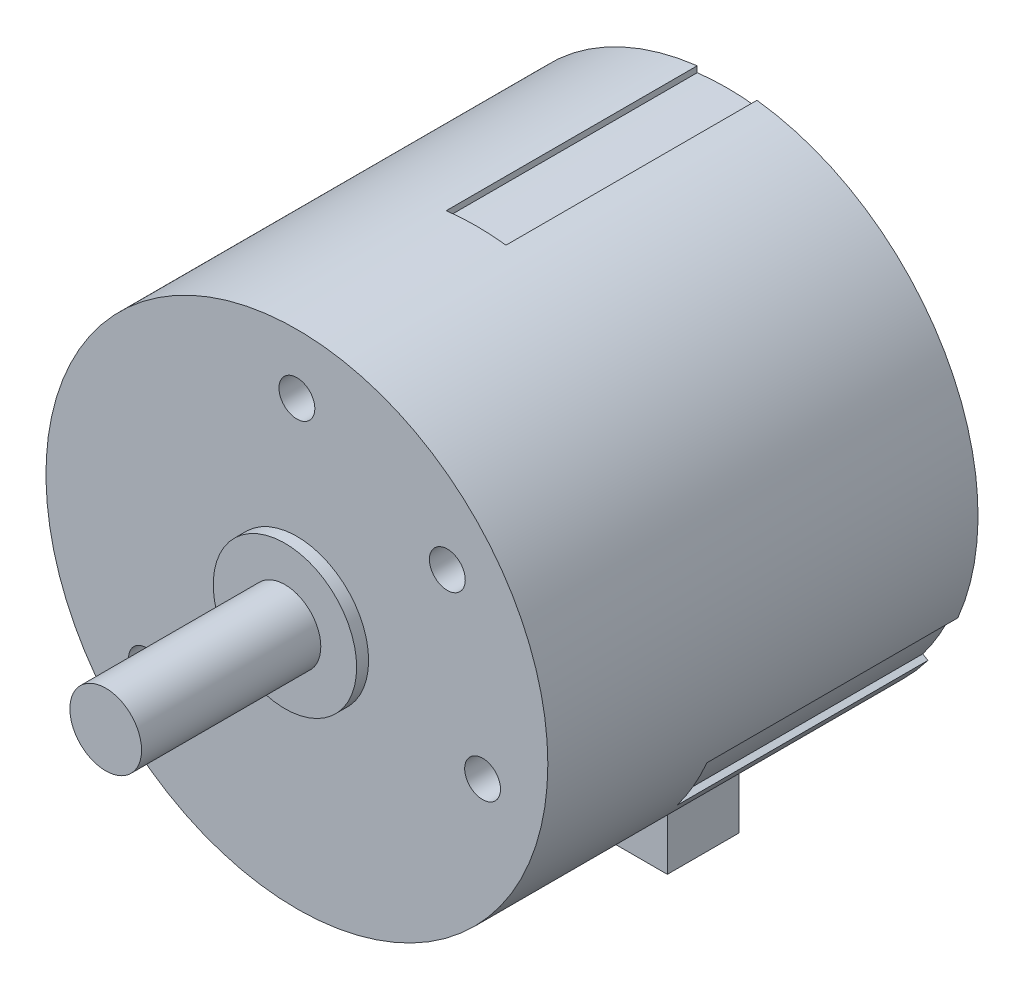
SolidWorks part; units mm, degrees
ref_plane "前视基准面" through (0, 0, 0) normal (0, 0, 1) x (1, 0, 0)
ref_plane "上视基准面" through (0, 0, 0) normal (0, 1, 0) x (1, 0, 0)
ref_plane "右视基准面" through (0, 0, 0) normal (1, 0, 0) x (0, 0, -1)
other "Configuration Table"
sketch "草图1" plane through (0, 0, 0) normal (0, 0, 1) x (1, 0, 0)
  circle A0 centre (0, 0) radius 21
extrude "凸台-拉伸1" add sketch "草图1" along normal blind 15
sketch "草图2" plane through (0, 0, 0) normal (0, 0, -1) x (-1, 0, 0)
  line L0 (2.5, 20.8507) -> (2.5, 20.347)
  line L1 (0, 8.25) -> (0, -8.25) construction
  line L2 (-2.5, 20.8507) -> (-2.5, 20.347)
  line L3 (19.3072, -8.2603) -> (18.871, -8.0084)
  line L4 (16.8072, -12.5904) -> (16.371, -12.3386)
  line L5 (-16.8072, -12.5904) -> (-16.371, -12.3386)
  line L6 (-19.3072, -8.2603) -> (-18.871, -8.0084)
  line L7 (15, -13.9732) -> (15, -14.6969)
  line L8 (-15, -13.9732) -> (-15, -14.6969)
  arc A0 (-2.5, 20.8507) -> (-19.3072, -8.2603) centre (0, 0) ccw
  circle A1 centre (0, 0) radius 21 construction
  arc A2 (-18.871, -8.0084) -> (-16.371, -12.3386) centre (0, 0) ccw
  arc A3 (19.3072, -8.2603) -> (2.5, 20.8507) centre (0, 0) ccw
  arc A4 (-16.8072, -12.5904) -> (-15, -14.6969) centre (0, 0) ccw
  arc A5 (15, -14.6969) -> (16.8072, -12.5904) centre (0, 0) ccw
  arc A6 (-15, -13.9732) -> (15, -13.9732) centre (0, 0) ccw
  arc A7 (16.371, -12.3386) -> (18.871, -8.0084) centre (0, 0) ccw
  arc A8 (2.5, 20.347) -> (-2.5, 20.347) centre (0, 0) ccw
  point P22 (0, 0)
  dimension "D1" = 5
  dimension "D2" = 3
  dimension "D3" = 30
extrude "凸台-拉伸2" add sketch "草图2" along normal blind 6
sketch "草图4" plane through (0, 0, -6) normal (0, 0, -1) x (-1, 0, 0)
  line L0 (10, -17.8955) -> (10, -24)
  line L1 (0, 11.55) -> (0, -11.55) construction
  line L2 (-10, -17.8955) -> (-10, -24)
  line L3 (-10, -24) -> (10, -24)
  line L8 (2.5, 20.8507) -> (2.5, 20.347)
  line L9 (-2.5, 20.347) -> (-2.5, 20.8507)
  line L10 (-19.3072, -8.2603) -> (-18.871, -8.0084)
  line L11 (-16.371, -12.3386) -> (-16.8072, -12.5904)
  line L12 (-15, -14.6969) -> (-15, -13.9732)
  line L13 (15, -13.9732) -> (15, -14.6969)
  line L14 (16.8072, -12.5904) -> (16.371, -12.3386)
  line L15 (18.871, -8.0084) -> (19.3072, -8.2603)
  line L16 (2.5, 20.8507) -> (2.5, 20.347)
  line L17 (-2.5, 20.347) -> (-2.5, 20.8507)
  line L18 (-19.3072, -8.2603) -> (-18.871, -8.0084)
  line L19 (-16.371, -12.3386) -> (-16.8072, -12.5904)
  line L20 (-15, -14.6969) -> (-15, -13.9732)
  line L21 (15, -13.9732) -> (15, -14.6969)
  line L22 (16.8072, -12.5904) -> (16.371, -12.3386)
  line L23 (18.871, -8.0084) -> (19.3072, -8.2603)
  arc A0 (10, -17.8955) -> (15, -13.9732) centre (0, 0) ccw
  arc A8 (19.3072, -8.2603) -> (2.5, 20.8507) centre (0, 0) ccw
  arc A9 (2.5, 20.347) -> (-2.5, 20.347) centre (0, 0) ccw
  arc A10 (-2.5, 20.8507) -> (-19.3072, -8.2603) centre (0, 0) ccw
  arc A11 (-18.871, -8.0084) -> (-16.371, -12.3386) centre (0, 0) ccw
  arc A12 (-16.8072, -12.5904) -> (-15, -14.6969) centre (0, 0) ccw
  arc A13 (-15, -13.9732) -> (15, -13.9732) centre (0, 0) ccw
  arc A14 (15, -14.6969) -> (16.8072, -12.5904) centre (0, 0) ccw
  arc A15 (16.371, -12.3386) -> (18.871, -8.0084) centre (0, 0) ccw
  arc A16 (19.3072, -8.2603) -> (2.5, 20.8507) centre (0, 0) ccw
  arc A17 (2.5, 20.347) -> (-2.5, 20.347) centre (0, 0) ccw
  arc A18 (-2.5, 20.8507) -> (-19.3072, -8.2603) centre (0, 0) ccw
  arc A19 (-18.871, -8.0084) -> (-16.371, -12.3386) centre (0, 0) ccw
  arc A20 (-16.8072, -12.5904) -> (-15, -14.6969) centre (0, 0) ccw
  arc A21 (-15, -13.9732) -> (-10, -17.8955) centre (0, 0) ccw
  arc A22 (15, -14.6969) -> (16.8072, -12.5904) centre (0, 0) ccw
  arc A23 (16.371, -12.3386) -> (18.871, -8.0084) centre (0, 0) ccw
  dimension "D2" = 20
  dimension "D3" = 24
  dimension "D1" = 0
extrude "凸台-拉伸3" add sketch "草图4" along normal blind 6
sketch "草图5" plane through (0, 0, -12) normal (0, 0, -1) x (-1, 0, 0)
  line L8 (18.871, -8.0084) -> (19.3072, -8.2603)
  line L9 (2.5, 20.8507) -> (2.5, 20.347)
  line L10 (-2.5, 20.347) -> (-2.5, 20.8507)
  line L11 (-19.3072, -8.2603) -> (-18.871, -8.0084)
  line L12 (-16.371, -12.3386) -> (-16.8072, -12.5904)
  line L13 (-15, -14.6969) -> (-15, -13.9732)
  line L14 (15, -13.9732) -> (15, -14.6969)
  line L15 (16.8072, -12.5904) -> (16.371, -12.3386)
  line L16 (18.871, -8.0084) -> (19.3072, -8.2603)
  line L17 (2.5, 20.8507) -> (2.5, 20.347)
  line L18 (-2.5, 20.347) -> (-2.5, 20.8507)
  line L19 (-19.3072, -8.2603) -> (-18.871, -8.0084)
  line L20 (-16.371, -12.3386) -> (-16.8072, -12.5904)
  line L23 (16.8072, -12.5904) -> (16.371, -12.3386)
  arc A0 (-15, -14.6969) -> (15, -14.6969) centre (0, 0) ccw
  arc A1 (-15, -14.6969) -> (15, -14.6969) centre (0, 0) ccw construction
  arc A8 (19.3072, -8.2603) -> (2.5, 20.8507) centre (0, 0) ccw
  arc A9 (2.5, 20.347) -> (-2.5, 20.347) centre (0, 0) ccw
  arc A10 (-2.5, 20.8507) -> (-19.3072, -8.2603) centre (0, 0) ccw
  arc A11 (-18.871, -8.0084) -> (-16.371, -12.3386) centre (0, 0) ccw
  arc A12 (-16.8072, -12.5904) -> (-15, -14.6969) centre (0, 0) ccw
  arc A13 (-15, -13.9732) -> (15, -13.9732) centre (0, 0) ccw
  arc A14 (15, -14.6969) -> (16.8072, -12.5904) centre (0, 0) ccw
  arc A15 (16.371, -12.3386) -> (18.871, -8.0084) centre (0, 0) ccw
  arc A16 (19.3072, -8.2603) -> (2.5, 20.8507) centre (0, 0) ccw
  arc A17 (2.5, 20.347) -> (-2.5, 20.347) centre (0, 0) ccw
  arc A18 (-2.5, 20.8507) -> (-19.3072, -8.2603) centre (0, 0) ccw
  arc A19 (-18.871, -8.0084) -> (-16.371, -12.3386) centre (0, 0) ccw
  arc A20 (-16.8072, -12.5904) -> (-15, -14.6969) centre (0, 0) ccw
  arc A22 (15, -14.6969) -> (16.8072, -12.5904) centre (0, 0) ccw
  arc A23 (16.371, -12.3386) -> (18.871, -8.0084) centre (0, 0) ccw
  dimension "D1" = 0
extrude "凸台-拉伸4" add sketch "草图5" along normal blind 9
sketch "草图6" plane through (0, 0, 15) normal (0, 0, 1) x (1, 0, 0)
  circle A0 centre (0, 0) radius 6
extrude "凸台-拉伸5" add sketch "草图6" along normal blind 1
sketch "草图7" plane through (0, 0, 16) normal (0, 0, 1) x (1, 0, 0)
  circle A0 centre (0, 0) radius 3
extrude "凸台-拉伸6" add sketch "草图7" along normal blind 15
sketch "草图8" plane through (0, 0, 15) normal (0, 0, 1) x (1, 0, 0)
  circle A0 centre (0, 0) radius 16 construction
  circle A1 centre (0, 16) radius 1.5
  circle A2 centre (12.5891, 9.875) radius 1.5
  circle A3 centre (15.5396, -3.8105) radius 1.5
  circle A4 centre (-12.5891, -9.875) radius 1.5
  point P14 (0, 0)
  dimension "D1" = 14
  dimension "D2" = 14
  dimension "D3" = 2
extrude "切除-拉伸1" cut sketch "草图8" against normal blind 3
